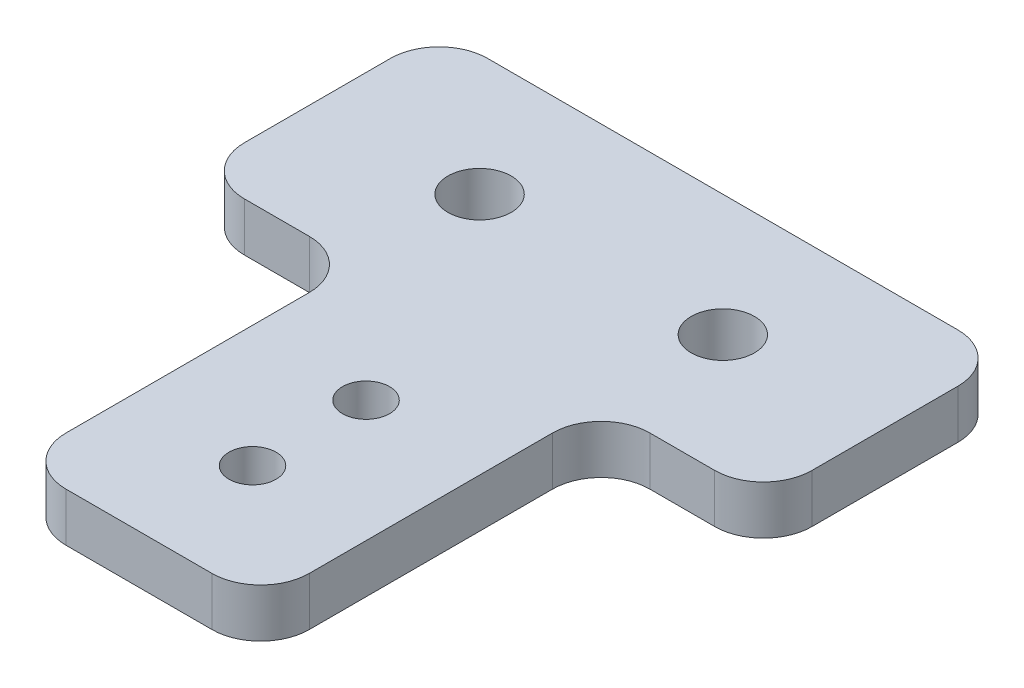
SolidWorks part; units mm, degrees
material "Thornel Mat VMA"
ref_plane "前视基准面" through (0, 0, 0) normal (0, 0, 1) x (1, 0, 0)
ref_plane "上视基准面" through (0, 0, 0) normal (0, 1, 0) x (1, 0, 0)
ref_plane "右视基准面" through (0, 0, 0) normal (1, 0, 0) x (0, 0, -1)
other "Configuration Table"
sketch "草图1" plane through (0, 0, 0) normal (0, 1, 0) x (1, 0, 0)
  line L0 (-25.8007, 0) -> (26.8643, 0) construction
  line L1 (-17.5, -7.5) -> (17.5, -7.5) construction
  line L2 (-17.5, -7.5) -> (-17.5, 7.5)
  line L3 (-17.5, 7.5) -> (17.5, 7.5)
  line L4 (17.5, -7.5) -> (17.5, 7.5)
  line L5 (-17.5, -7.5) -> (17.5, 7.5) construction
  line L6 (-17.5, 7.5) -> (17.5, -7.5) construction
  line L7 (-7.5, -7.5) -> (7.5, -7.5) construction
  line L8 (-7.5, -7.5) -> (-7.5, -28.5)
  line L9 (-7.5, -28.5) -> (7.5, -28.5)
  line L10 (7.5, -7.5) -> (7.5, -28.5)
  line L11 (0, 14.3215) -> (0, -29.1125) construction
  line L12 (-17.5, -7.5) -> (-7.5, -7.5)
  line L13 (7.5, -7.5) -> (17.5, -7.5)
  circle A0 centre (0, -14.5) radius 1.45
  circle A1 centre (0, -21.5) radius 1.45
  circle A2 centre (-7.5, 0) radius 1.95
  circle A3 centre (7.5, 0) radius 1.95
  point P0 (0, 0)
  dimension "D3" = 7
  dimension "D4" = 7
  dimension "D5" = 7
  dimension "D6" = 2.9
  dimension "D7" = 15
  dimension "D9" = 3.9
  dimension "D1" = 15
  dimension "D2" = 15
  dimension "D8" = 35
extrude "凸台-拉伸1" add sketch "草图1" along normal blind 3
fillet "圆角2" radius 3 8 edges at (7.5, 1.5, 28.5) (-7.5, 1.5, 28.5) (-7.5, 1.5, 7.5) (-17.5, 1.5, 7.5) (-17.5, 1.5, -7.5) (17.5, 1.5, -7.5) (17.5, 1.5, 7.5) (7.5, 1.5, 7.5)
